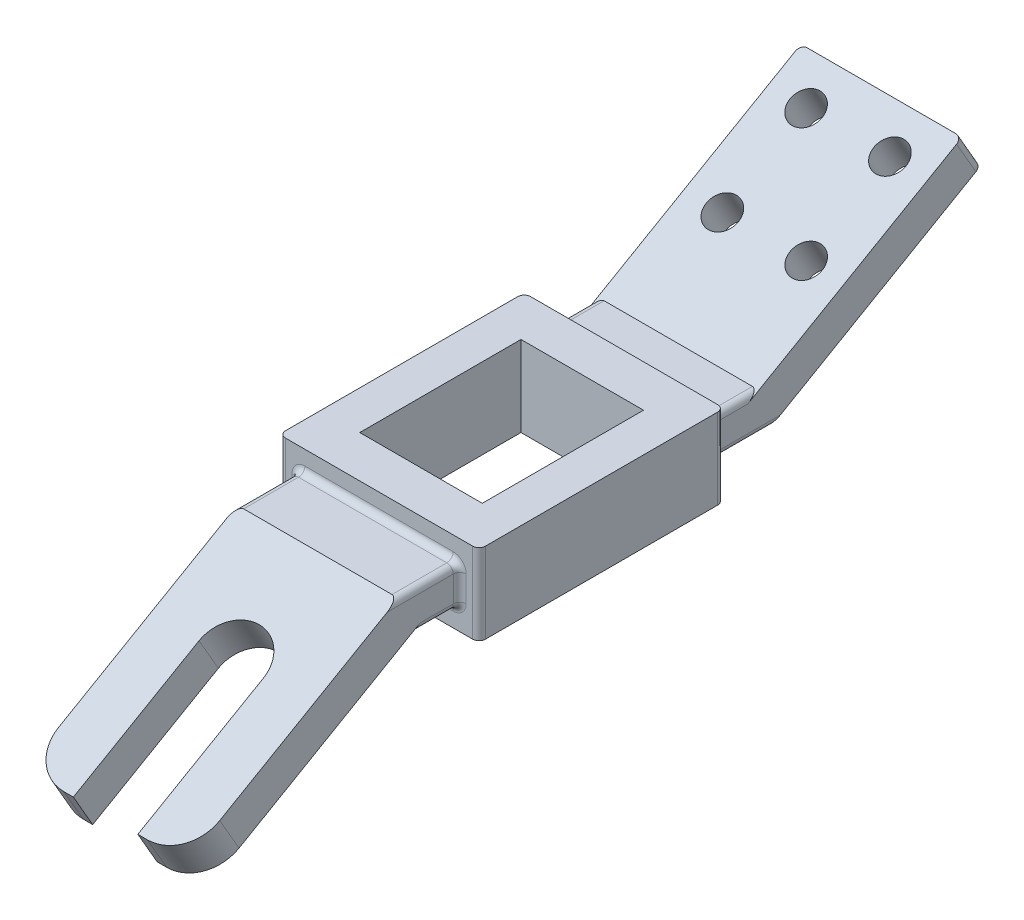
SolidWorks part; units mm, degrees
ref_plane "前基準面" through (0, 0, 0) normal (0, 0, 1) x (1, 0, 0)
ref_plane "上基準面" through (0, 0, 0) normal (0, 1, 0) x (1, 0, 0)
ref_plane "右基準面" through (0, 0, 0) normal (1, 0, 0) x (0, 0, -1)
sketch "草圖1" plane through (0, 0, 0) normal (0, 1, 0) x (1, 0, 0)
  line L0 (-31, 38) -> (31, -38) construction
  line L1 (-31, 38) -> (31, 38)
  line L2 (-31, 38) -> (-31, -38)
  line L3 (-31, -38) -> (31, -38)
  line L4 (31, 38) -> (31, -38)
  line L5 (-19, -25) -> (19, 25) construction
  line L6 (-19, 25) -> (19, 25)
  line L7 (-19, 25) -> (-19, -25)
  line L8 (-19, -25) -> (19, -25)
  line L9 (19, 25) -> (19, -25)
  dimension "D1" = 76
  dimension "D2" = 62
  dimension "D3" = 50
  dimension "D4" = 38
extrude "伸長1" add sketch "草圖1" along normal mid plane 25
sketch "草圖2" plane through (0, 0, 0) normal (1, 0, 0) x (0, 0, -1)
  line L0 (0, 0) -> (64.3009, 0) construction
  line L1 (38, 6) -> (54.7846, 6)
  line L2 (38, 12.5) -> (38, -12.5) construction
  line L3 (54.7846, 6) -> (117.8179, 42.3923)
  line L4 (117.8179, 42.3923) -> (123.8179, 32)
  line L5 (123.8179, 32) -> (58, -6)
  line L6 (58, -6) -> (38, -6)
  line L7 (38, -6) -> (38, 6)
  line L8 (-38, 6) -> (-57, 6)
  line L9 (-38, 12.5) -> (-38, -12.5) construction
  line L10 (-57, 6) -> (-122.8179, -32)
  line L11 (-122.8179, -32) -> (-116.8179, -42.3923)
  line L12 (-116.8179, -42.3923) -> (-53.7846, -6)
  line L13 (-53.7846, -6) -> (-38, -6)
  line L14 (-38, -6) -> (-38, 6)
  dimension "D1" = 12
  dimension "D2" = 30
  dimension "D3" = 76
  dimension "D4" = 12
  dimension "D5" = 20
  dimension "D6" = 19
  dimension "D7" = 76
  dimension "D8" = 12
  dimension "D9" = 30
extrude "伸長2" add sketch "草圖2" along normal mid plane 50
sketch "草圖3" plane through (0, -19.2224, -11.0981) normal (0, 0.866, 0.5) x (1, 0, 0)
  line L0 (-13, 111.2295) -> (-13, 81.2295) construction
  line L1 (-13, 111.2295) -> (13, 111.2295) construction
  line L2 (-13, 81.2295) -> (13, 81.2295) construction
  line L3 (13, 111.2295) -> (13, 81.2295) construction
  line L4 (-25, 123.2295) -> (-25, 50.4449) construction
  line L5 (25, 123.2295) -> (-25, 123.2295) construction
  circle A0 centre (-13, 111.2295) radius 5
  circle A1 centre (13, 111.2295) radius 5
  circle A2 centre (-13, 81.2295) radius 5
  circle A3 centre (13, 81.2295) radius 5
  dimension "D2" = 10
  dimension "D1" = 12
  dimension "D3" = 26
  dimension "D4" = 12
  dimension "D5" = 30
extrude "伸長3" cut sketch "草圖3" against normal through all
sketch "草圖4" plane through (0, 29.1817, 16.8481) normal (0, 0.866, 0.5) x (1, 0, 0)
  line L0 (-10, -122.3634) -> (-10, -77.3634)
  line L1 (25, -122.3634) -> (-25, -122.3634) construction
  line L2 (10, -77.3634) -> (10, -122.3634)
  line L3 (10, -122.3634) -> (-10, -122.3634)
  line L4 (0, 0) -> (0, -77.3634) construction
  arc A0 (-10, -77.3634) -> (10, -77.3634) centre (0, -77.3634) cw
  dimension "D1" = 20
  dimension "D2" = 45
extrude "伸長4" cut sketch "草圖4" against normal through all
fillet "圓角1" radius 12 2 edges at (-25, -37.1962, 119.8179) (25, -37.1962, 119.8179)
fillet "圓角2" radius 2 14 edges at (-25, -6, -48) (-25, 6, -46.3923) (25, -6, -48) (25, 6, -46.3923) (-25, 37.1962, -120.8179) (25, 37.1962, -120.8179) (-25, -6, 45.8923) (-25, 6, 47.5) (25, -6, 45.8923) (25, 6, 47.5) (-31, 0, 38) (-31, 0, -38) (31, 0, -38) (31, 0, 38)
fillet "圓角3" radius 2 16 edges at (24.4142, 5.4142, -38) (25, 0, -38) (24.4142, -5.4142, -38) (0, -6, -38) (-24.4142, -5.4142, -38) (-25, 0, -38) (-24.4142, 5.4142, -38) (24.4142, 5.4142, 38) (25, 0, 38) (24.4142, -5.4142, 38) (0, -6, 38) (-24.4142, -5.4142, 38) (-25, 0, 38) (-24.4142, 5.4142, 38) (0, 6, -38) (0, 6, 38)
